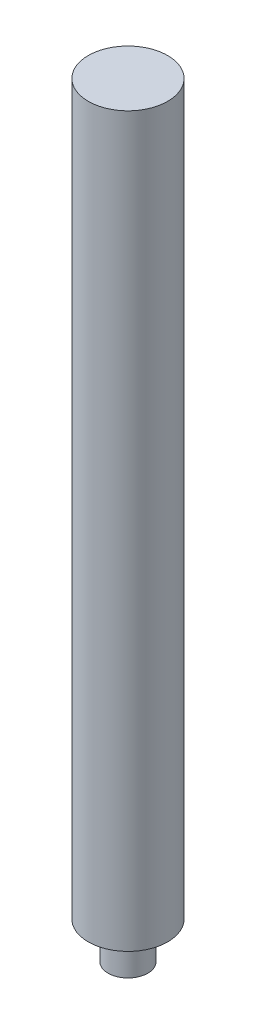
SolidWorks part; units mm, degrees
ref_plane "前基準面" through (0, 0, 0) normal (0, 0, 1) x (1, 0, 0)
ref_plane "上基準面" through (0, 0, 0) normal (0, 1, 0) x (1, 0, 0)
ref_plane "右基準面" through (0, 0, 0) normal (1, 0, 0) x (0, 0, -1)
sketch "草圖1" plane through (0, 0, 0) normal (0, 1, 0) x (1, 0, 0)
  circle A0 centre (0, 0) radius 1.5
extrude "填料-伸長1" add sketch "草圖1" along normal blind 2.8
sketch "草圖2" plane through (0, 2.8, 0) normal (0, 1, 0) x (1, 0, 0)
  circle A0 centre (0, 0) radius 3
extrude "填料-伸長2" add sketch "草圖2" along normal blind 55
